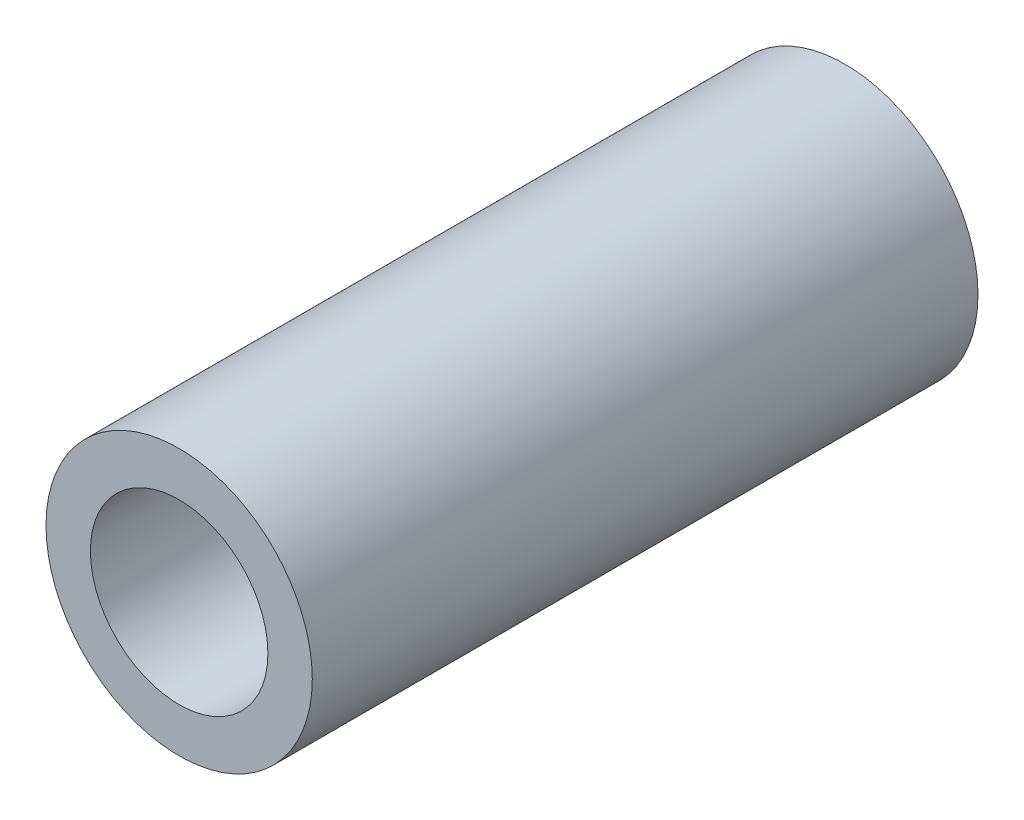
SolidWorks part; units mm, degrees
ref_plane "前视基准面" through (0, 0, 0) normal (0, 0, 1) x (1, 0, 0)
ref_plane "上视基准面" through (0, 0, 0) normal (0, 1, 0) x (1, 0, 0)
ref_plane "右视基准面" through (0, 0, 0) normal (1, 0, 0) x (0, 0, -1)
sketch "草图1" plane through (0, 0, 0) normal (0, 0, 1) x (1, 0, 0)
  circle A0 centre (0, 0) radius 3
  circle A1 centre (0, 0) radius 2
  dimension "D1" = 4
  dimension "D2" = 6
extrude "凸台-拉伸1" add sketch "草图1" along normal mid plane 15
